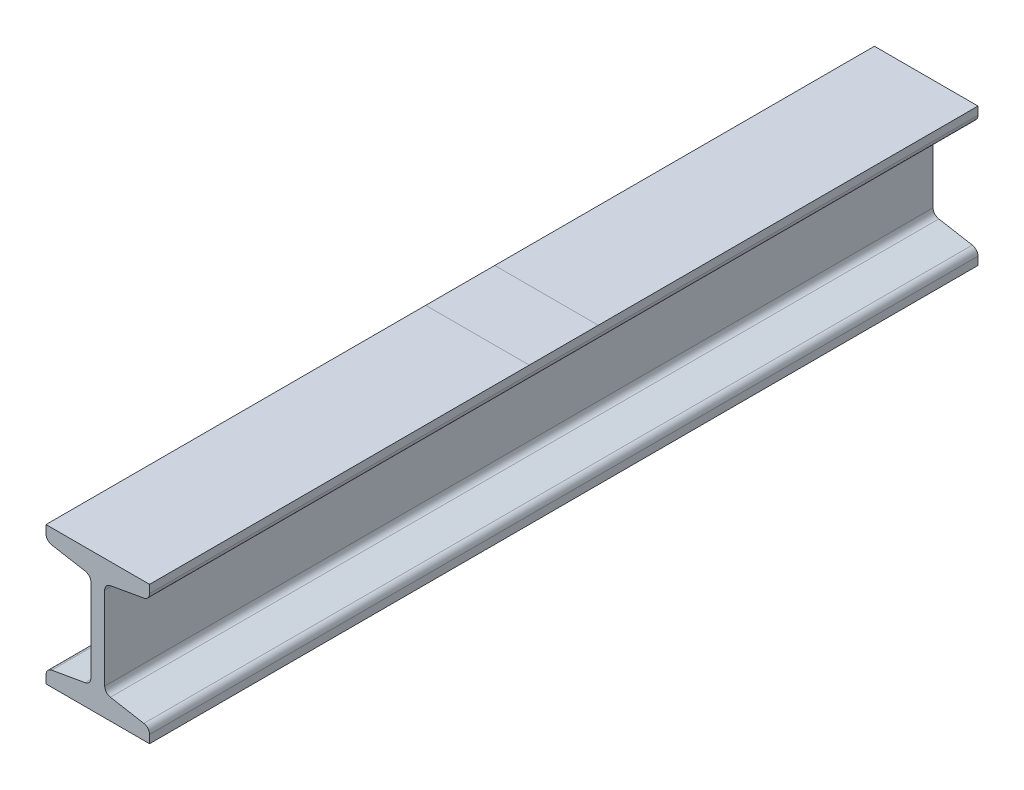
SolidWorks part; units mm, degrees
ref_plane "Front Plane" through (0, 0, 0) normal (0, 0, 1) x (1, 0, 0)
ref_plane "Top Plane" through (0, 0, 0) normal (0, 1, 0) x (1, 0, 0)
ref_plane "Right Plane" through (0, 0, 0) normal (1, 0, 0) x (0, 0, -1)
sketch "Sketch1" plane through (0, 0, 0) normal (0, 0, 1) x (1, 0, 0)
  line L0 (0, 75.4455) -> (0, -52.0857) construction
  line L12 (-37.5, 50) -> (37.5, 50)
  line L17 (-5, -34.2694) -> (-5, 34.2694)
  line L19 (5, -34.2694) -> (5, 34.2694)
  line L20 (-32.6398, 0) -> (37.5, 0) construction
  line L21 (37.5, -50) -> (37.5, -40)
  line L22 (37.5, 50) -> (37.5, 40)
  line L23 (37.5, 40) -> (5, 34.2694)
  line L24 (-37.5, 50) -> (-37.5, 40)
  line L25 (-37.5, 40) -> (-5, 34.2694)
  line L26 (37.5, -40) -> (5, -34.2694)
  line L27 (-37.5, -50) -> (37.5, -50)
  line L28 (-37.5, -50) -> (-37.5, -40)
  line L29 (-37.5, -40) -> (-5, -34.2694)
  point P3 (0, 0)
  point P11 (0, 50)
  dimension "D1" = 10
  dimension "D2" = 100
  dimension "D3" = 100
  dimension "D4" = 75
  dimension "D5" = 10
  dimension "D6" = 100
extrude "Boss-Extrude1" add sketch "Sketch1" along normal blind 600
sketch "Sketch2" plane through (0, 50, 0) normal (0, 1, 0) x (1, 0, 0)
  line L0 (37.5, -600) -> (37.5, 0) construction
  line L1 (-37.5, -325) -> (37.5, -325)
  line L2 (-37.5, -325) -> (-37.5, -275)
  line L3 (-37.5, -275) -> (37.5, -275)
  line L4 (37.5, -325) -> (37.5, -275)
  line L5 (-37.5, -325) -> (37.5, -275) construction
  line L6 (-37.5, -275) -> (37.5, -325) construction
  point P0 (0, -300)
  dimension "D1" = 300
  dimension "D2" = 50
  dimension "D3" = 75
split line "Split Line1"
sketch "Sketch3" plane through (0, -50, 0) normal (0, -1, 0) x (1, 0, 0)
  line L0 (37.5, 600) -> (37.5, 0) construction
  line L1 (-37.5, 600) -> (37.5, 600)
  line L2 (-37.5, 600) -> (-37.5, 560)
  line L3 (-37.5, 560) -> (37.5, 560)
  line L4 (37.5, 600) -> (37.5, 560)
  line L5 (-37.5, 600) -> (-37.5, 0) construction
  line L6 (37.5, 0) -> (-37.5, 0)
  line L7 (37.5, 0) -> (37.5, 40)
  line L8 (37.5, 40) -> (-37.5, 40)
  line L9 (-37.5, 0) -> (-37.5, 40)
  dimension "D1" = 40
  dimension "D2" = 40
split line "Split Line2"
fillet "Fillet1" radius 5 8 edges at (37.5, -40, 300) (37.5, 40, 300) (-37.5, 40, 300) (-37.5, -40, 300) (5, -34.2694, 300) (-5, -34.2694, 300) (5, 34.2694, 300) (-5, 34.2694, 300)
